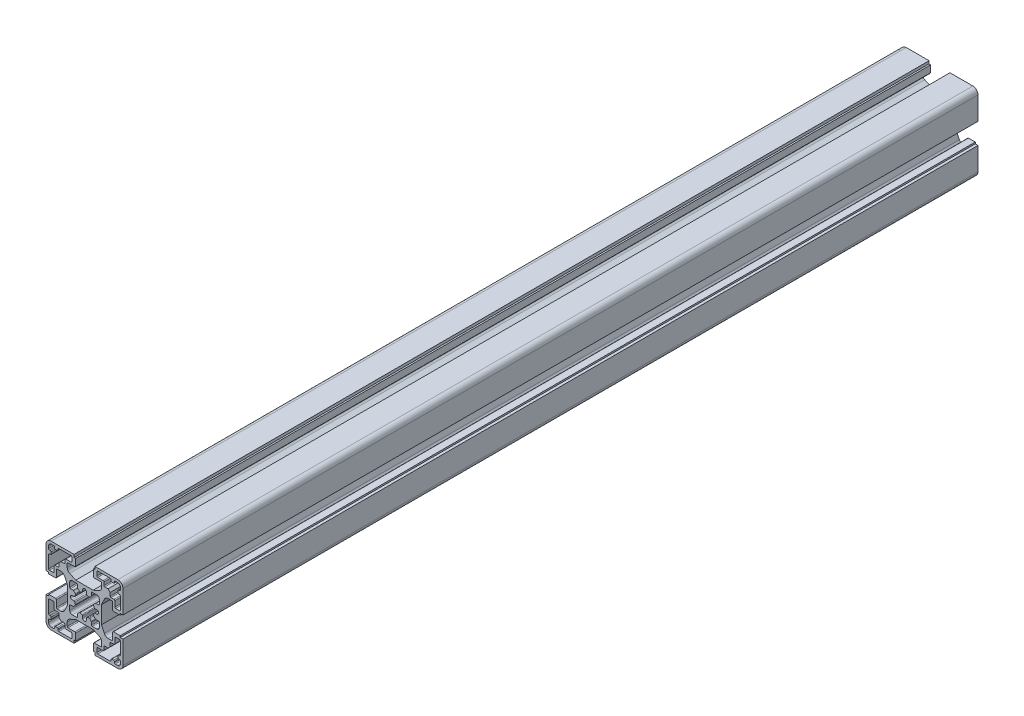
SolidWorks part; units mm, degrees
ref_plane "Alzado" through (0, 0, 0) normal (0, 0, 1) x (1, 0, 0)
ref_plane "Planta" through (0, 0, 0) normal (0, 1, 0) x (1, 0, 0)
ref_plane "Vista lateral" through (0, 0, 0) normal (1, 0, 0) x (0, 0, -1)
ref_plane "Plano1" through (0, 0, 1312.5) normal (0, 0, 1) x (1, 0, 0)
sketch "Croquis1" plane through (0, 0, 1312.5) normal (0, 0, 1) x (1, 0, 0)
  line L0 (13.7574, 15) -> (11.9, 15)
  line L1 (11.4, 15.5) -> (11.4, 17.25)
  line L2 (10.9, 17.75) -> (7.775, 17.75)
  line L3 (7.275, 18.25) -> (7.275, 20.5)
  line L4 (7.775, 21) -> (15, 21)
  line L5 (15.5, 20.5) -> (15.5, 20)
  line L6 (16, 19.5) -> (17, 19.5)
  line L7 (17.5, 20) -> (17.5, 20.5)
  line L8 (18, 21) -> (19.4, 21)
  line L9 (21, 19.4) -> (21, 18)
  line L10 (20.5, 17.5) -> (20, 17.5)
  line L11 (19.5, 17) -> (19.5, 16)
  line L12 (20, 15.5) -> (20.5, 15.5)
  line L13 (21, 15) -> (21, 7.775)
  line L14 (20.5, 7.275) -> (18.25, 7.275)
  line L15 (17.75, 7.775) -> (17.75, 10.9)
  line L16 (17.25, 11.4) -> (15.5, 11.4)
  line L17 (15, 11.9) -> (15, 13.7574)
  line L18 (15, 13.7574) -> (13.7574, 15)
  line L19 (-11.4, 17.25) -> (-11.4, 15.5)
  line L20 (-11.9, 15) -> (-13.7574, 15)
  line L21 (-13.7574, 15) -> (-15, 13.7574)
  line L22 (-15, 13.7574) -> (-15, 11.9)
  line L23 (-15.5, 11.4) -> (-17.25, 11.4)
  line L24 (-17.75, 10.9) -> (-17.75, 7.775)
  line L25 (-18.25, 7.275) -> (-20.5, 7.275)
  line L26 (-21, 7.775) -> (-21, 15)
  line L27 (-20.5, 15.5) -> (-20, 15.5)
  line L28 (-19.5, 16) -> (-19.5, 17)
  line L29 (-20, 17.5) -> (-20.5, 17.5)
  line L30 (-21, 18) -> (-21, 19.4)
  line L31 (-19.4, 21) -> (-18, 21)
  line L32 (-17.5, 20.5) -> (-17.5, 20)
  line L33 (-17, 19.5) -> (-16, 19.5)
  line L34 (-15.5, 20) -> (-15.5, 20.5)
  line L35 (-15, 21) -> (-7.775, 21)
  line L36 (-7.275, 20.5) -> (-7.275, 18.25)
  line L37 (-7.775, 17.75) -> (-10.9, 17.75)
  line L38 (-20.5, -7.275) -> (-18.25, -7.275)
  line L39 (-17.75, -7.775) -> (-17.75, -10.9)
  line L40 (-17.25, -11.4) -> (-15.5, -11.4)
  line L41 (-15, -11.9) -> (-15, -13.7574)
  line L42 (-15, -13.7574) -> (-13.7574, -15)
  line L43 (-13.7574, -15) -> (-11.9, -15)
  line L44 (-11.4, -15.5) -> (-11.4, -17.25)
  line L45 (-10.9, -17.75) -> (-7.775, -17.75)
  line L46 (-7.275, -18.25) -> (-7.275, -20.5)
  line L47 (-7.775, -21) -> (-15, -21)
  line L48 (-15.5, -20.5) -> (-15.5, -20)
  line L49 (-16, -19.5) -> (-17, -19.5)
  line L50 (-17.5, -20) -> (-17.5, -20.5)
  line L51 (-18, -21) -> (-19.4, -21)
  line L52 (-21, -19.4) -> (-21, -18)
  line L53 (-20.5, -17.5) -> (-20, -17.5)
  line L54 (-19.5, -17) -> (-19.5, -16)
  line L55 (-20, -15.5) -> (-20.5, -15.5)
  line L56 (-21, -15) -> (-21, -7.775)
  line L57 (-20.9, -6.1) -> (-22.5, -6.1)
  line L58 (-22.5, -6.1) -> (-22.5, -19.5)
  line L59 (-19.5, -22.5) -> (-6.1, -22.5)
  line L60 (-6.1, -22.5) -> (-6.1, -20.9)
  line L61 (-6.1, -20.9) -> (-5.175, -20.9)
  line L62 (-5.175, -20.9) -> (-5.175, -16.95)
  line L63 (-5.675, -16.45) -> (-9.6, -16.45)
  line L64 (-10.1, -15.95) -> (-10.1, -13.8742)
  line L65 (-8.6565, -11.6084) -> (-5.1, -9.95)
  line L66 (-5.1, -9.95) -> (5.1, -9.95)
  line L67 (5.1, -9.95) -> (8.6565, -11.6084)
  line L68 (10.1, -13.8742) -> (10.1, -15.95)
  line L69 (9.6, -16.45) -> (5.675, -16.45)
  line L70 (5.175, -16.95) -> (5.175, -20.9)
  line L71 (5.175, -20.9) -> (6.1, -20.9)
  line L72 (6.1, -20.9) -> (6.1, -22.5)
  line L73 (6.1, -22.5) -> (19.5, -22.5)
  line L74 (22.5, -19.5) -> (22.5, -6.1)
  line L75 (22.5, -6.1) -> (20.9, -6.1)
  line L76 (20.9, -6.1) -> (20.9, -5.175)
  line L77 (20.9, -5.175) -> (16.95, -5.175)
  line L78 (16.45, -5.675) -> (16.45, -9.6)
  line L79 (15.95, -10.1) -> (13.8742, -10.1)
  line L80 (11.6084, -8.6565) -> (9.95, -5.1)
  line L81 (9.95, -5.1) -> (9.95, 5.1)
  line L82 (9.95, 5.1) -> (11.6084, 8.6565)
  line L83 (13.8742, 10.1) -> (15.95, 10.1)
  line L84 (16.45, 9.6) -> (16.45, 5.675)
  line L85 (16.95, 5.175) -> (20.9, 5.175)
  line L86 (20.9, 5.175) -> (20.9, 6.1)
  line L87 (20.9, 6.1) -> (22.5, 6.1)
  line L88 (22.5, 6.1) -> (22.5, 19.5)
  line L89 (19.5, 22.5) -> (6.1, 22.5)
  line L90 (6.1, 22.5) -> (6.1, 20.9)
  line L91 (6.1, 20.9) -> (5.175, 20.9)
  line L92 (5.175, 20.9) -> (5.175, 16.95)
  line L93 (5.675, 16.45) -> (9.6, 16.45)
  line L94 (10.1, 15.95) -> (10.1, 13.8742)
  line L95 (8.6565, 11.6084) -> (5.1, 9.95)
  line L96 (5.1, 9.95) -> (-5.1, 9.95)
  line L97 (-5.1, 9.95) -> (-8.6565, 11.6084)
  line L98 (-10.1, 13.8742) -> (-10.1, 15.95)
  line L99 (-9.6, 16.45) -> (-5.675, 16.45)
  line L100 (-5.175, 16.95) -> (-5.175, 20.9)
  line L101 (-5.175, 20.9) -> (-6.1, 20.9)
  line L102 (-6.1, 20.9) -> (-6.1, 22.5)
  line L103 (-6.1, 22.5) -> (-19.5, 22.5)
  line L104 (-22.5, 19.5) -> (-22.5, 6.1)
  line L105 (-22.5, 6.1) -> (-20.9, 6.1)
  line L106 (-20.9, 6.1) -> (-20.9, 5.175)
  line L107 (-20.9, 5.175) -> (-16.95, 5.175)
  line L108 (-16.45, 5.675) -> (-16.45, 9.6)
  line L109 (-15.95, 10.1) -> (-13.8742, 10.1)
  line L110 (-11.6084, 8.6565) -> (-9.95, 5.1)
  line L111 (-9.95, 5.1) -> (-9.95, -5.1)
  line L112 (-9.95, -5.1) -> (-11.6084, -8.6565)
  line L113 (-13.8742, -10.1) -> (-15.95, -10.1)
  line L114 (-16.45, -9.6) -> (-16.45, -5.675)
  line L115 (-16.95, -5.175) -> (-20.9, -5.175)
  line L116 (-20.9, -5.175) -> (-20.9, -6.1)
  line L117 (-8.15, -4.1) -> (-6.7113, -4.1)
  line L118 (-6.3577, -3.9536) -> (-5.4141, -3.01)
  line L119 (-6.1451, -1.1) -> (-7.15, -1.1)
  line L120 (-7.15, 1.1) -> (-6.1451, 1.1)
  line L121 (-5.4141, 3.01) -> (-6.3577, 3.9536)
  line L122 (-6.7113, 4.1) -> (-8.15, 4.1)
  line L123 (-8.65, 4.6) -> (-8.65, 7.15)
  line L124 (-7.15, 8.65) -> (-4.6, 8.65)
  line L125 (-4.1, 8.15) -> (-4.1, 6.7113)
  line L126 (-3.9536, 6.3577) -> (-3.01, 5.4141)
  line L127 (-1.1, 6.1451) -> (-1.1, 7.15)
  line L128 (1.1, 7.15) -> (1.1, 6.1451)
  line L129 (3.01, 5.4141) -> (3.9536, 6.3577)
  line L130 (4.1, 6.7113) -> (4.1, 8.15)
  line L131 (4.6, 8.65) -> (7.15, 8.65)
  line L132 (8.65, 7.15) -> (8.65, 4.6)
  line L133 (8.15, 4.1) -> (6.7113, 4.1)
  line L134 (6.3577, 3.9536) -> (5.4141, 3.01)
  line L135 (6.1451, 1.1) -> (7.15, 1.1)
  line L136 (7.15, -1.1) -> (6.1451, -1.1)
  line L137 (5.4141, -3.01) -> (6.3577, -3.9536)
  line L138 (6.7113, -4.1) -> (8.15, -4.1)
  line L139 (8.65, -4.6) -> (8.65, -7.15)
  line L140 (7.15, -8.65) -> (4.6, -8.65)
  line L141 (4.1, -8.15) -> (4.1, -6.7113)
  line L142 (3.9536, -6.3577) -> (3.01, -5.4141)
  line L143 (1.1, -6.1451) -> (1.1, -7.15)
  line L144 (-1.1, -7.15) -> (-1.1, -6.1451)
  line L145 (-3.01, -5.4141) -> (-3.9536, -6.3577)
  line L146 (-4.1, -6.7113) -> (-4.1, -8.15)
  line L147 (-4.6, -8.65) -> (-7.15, -8.65)
  line L148 (-8.65, -7.15) -> (-8.65, -4.6)
  line L149 (11.9, -15) -> (13.7574, -15)
  line L150 (13.7574, -15) -> (15, -13.7574)
  line L151 (15, -13.7574) -> (15, -11.9)
  line L152 (15.5, -11.4) -> (17.25, -11.4)
  line L153 (17.75, -10.9) -> (17.75, -7.775)
  line L154 (18.25, -7.275) -> (20.5, -7.275)
  line L155 (21, -7.775) -> (21, -15)
  line L156 (20.5, -15.5) -> (20, -15.5)
  line L157 (19.5, -16) -> (19.5, -17)
  line L158 (20, -17.5) -> (20.5, -17.5)
  line L159 (21, -18) -> (21, -19.4)
  line L160 (19.4, -21) -> (18, -21)
  line L161 (17.5, -20.5) -> (17.5, -20)
  line L162 (17, -19.5) -> (16, -19.5)
  line L163 (15.5, -20) -> (15.5, -20.5)
  line L164 (15, -21) -> (7.775, -21)
  line L165 (7.275, -20.5) -> (7.275, -18.25)
  line L166 (7.775, -17.75) -> (10.9, -17.75)
  line L167 (11.4, -17.25) -> (11.4, -15.5)
  arc A0 (11.9, 15) -> (11.4, 15.5) centre (11.9, 15.5) cw
  arc A1 (11.4, 17.25) -> (10.9, 17.75) centre (10.9, 17.25) ccw
  arc A2 (7.775, 17.75) -> (7.275, 18.25) centre (7.775, 18.25) cw
  arc A3 (7.275, 20.5) -> (7.775, 21) centre (7.775, 20.5) cw
  arc A4 (15, 21) -> (15.5, 20.5) centre (15, 20.5) cw
  arc A5 (15.5, 20) -> (16, 19.5) centre (16, 20) ccw
  arc A6 (17, 19.5) -> (17.5, 20) centre (17, 20) ccw
  arc A7 (17.5, 20.5) -> (18, 21) centre (18, 20.5) cw
  arc A8 (19.4, 21) -> (21, 19.4) centre (19.4, 19.4) cw
  arc A9 (21, 18) -> (20.5, 17.5) centre (20.5, 18) cw
  arc A10 (20, 17.5) -> (19.5, 17) centre (20, 17) ccw
  arc A11 (19.5, 16) -> (20, 15.5) centre (20, 16) ccw
  arc A12 (20.5, 15.5) -> (21, 15) centre (20.5, 15) cw
  arc A13 (21, 7.775) -> (20.5, 7.275) centre (20.5, 7.775) cw
  arc A14 (18.25, 7.275) -> (17.75, 7.775) centre (18.25, 7.775) cw
  arc A15 (17.75, 10.9) -> (17.25, 11.4) centre (17.25, 10.9) ccw
  arc A16 (15.5, 11.4) -> (15, 11.9) centre (15.5, 11.9) cw
  arc A17 (-10.9, 17.75) -> (-11.4, 17.25) centre (-10.9, 17.25) ccw
  arc A18 (-11.4, 15.5) -> (-11.9, 15) centre (-11.9, 15.5) cw
  arc A19 (-15, 11.9) -> (-15.5, 11.4) centre (-15.5, 11.9) cw
  arc A20 (-17.25, 11.4) -> (-17.75, 10.9) centre (-17.25, 10.9) ccw
  arc A21 (-17.75, 7.775) -> (-18.25, 7.275) centre (-18.25, 7.775) cw
  arc A22 (-20.5, 7.275) -> (-21, 7.775) centre (-20.5, 7.775) cw
  arc A23 (-21, 15) -> (-20.5, 15.5) centre (-20.5, 15) cw
  arc A24 (-20, 15.5) -> (-19.5, 16) centre (-20, 16) ccw
  arc A25 (-19.5, 17) -> (-20, 17.5) centre (-20, 17) ccw
  arc A26 (-20.5, 17.5) -> (-21, 18) centre (-20.5, 18) cw
  arc A27 (-21, 19.4) -> (-19.4, 21) centre (-19.4, 19.4) cw
  arc A28 (-18, 21) -> (-17.5, 20.5) centre (-18, 20.5) cw
  arc A29 (-17.5, 20) -> (-17, 19.5) centre (-17, 20) ccw
  arc A30 (-16, 19.5) -> (-15.5, 20) centre (-16, 20) ccw
  arc A31 (-15.5, 20.5) -> (-15, 21) centre (-15, 20.5) cw
  arc A32 (-7.775, 21) -> (-7.275, 20.5) centre (-7.775, 20.5) cw
  arc A33 (-7.275, 18.25) -> (-7.775, 17.75) centre (-7.775, 18.25) cw
  arc A34 (-18.25, -7.275) -> (-17.75, -7.775) centre (-18.25, -7.775) cw
  arc A35 (-17.75, -10.9) -> (-17.25, -11.4) centre (-17.25, -10.9) ccw
  arc A36 (-15.5, -11.4) -> (-15, -11.9) centre (-15.5, -11.9) cw
  arc A37 (-11.9, -15) -> (-11.4, -15.5) centre (-11.9, -15.5) cw
  arc A38 (-11.4, -17.25) -> (-10.9, -17.75) centre (-10.9, -17.25) ccw
  arc A39 (-7.775, -17.75) -> (-7.275, -18.25) centre (-7.775, -18.25) cw
  arc A40 (-7.275, -20.5) -> (-7.775, -21) centre (-7.775, -20.5) cw
  arc A41 (-15, -21) -> (-15.5, -20.5) centre (-15, -20.5) cw
  arc A42 (-15.5, -20) -> (-16, -19.5) centre (-16, -20) ccw
  arc A43 (-17, -19.5) -> (-17.5, -20) centre (-17, -20) ccw
  arc A44 (-17.5, -20.5) -> (-18, -21) centre (-18, -20.5) cw
  arc A45 (-19.4, -21) -> (-21, -19.4) centre (-19.4, -19.4) cw
  arc A46 (-21, -18) -> (-20.5, -17.5) centre (-20.5, -18) cw
  arc A47 (-20, -17.5) -> (-19.5, -17) centre (-20, -17) ccw
  arc A48 (-19.5, -16) -> (-20, -15.5) centre (-20, -16) ccw
  arc A49 (-20.5, -15.5) -> (-21, -15) centre (-20.5, -15) cw
  arc A50 (-21, -7.775) -> (-20.5, -7.275) centre (-20.5, -7.775) cw
  arc A51 (-22.5, -19.5) -> (-19.5, -22.5) centre (-19.5, -19.5) ccw
  arc A52 (-5.175, -16.95) -> (-5.675, -16.45) centre (-5.675, -16.95) ccw
  arc A53 (-9.6, -16.45) -> (-10.1, -15.95) centre (-9.6, -15.95) cw
  arc A54 (-10.1, -13.8742) -> (-8.6565, -11.6084) centre (-7.6, -13.8742) cw
  arc A55 (8.6565, -11.6084) -> (10.1, -13.8742) centre (7.6, -13.8742) cw
  arc A56 (10.1, -15.95) -> (9.6, -16.45) centre (9.6, -15.95) cw
  arc A57 (5.675, -16.45) -> (5.175, -16.95) centre (5.675, -16.95) ccw
  arc A58 (19.5, -22.5) -> (22.5, -19.5) centre (19.5, -19.5) ccw
  arc A59 (16.95, -5.175) -> (16.45, -5.675) centre (16.95, -5.675) ccw
  arc A60 (16.45, -9.6) -> (15.95, -10.1) centre (15.95, -9.6) cw
  arc A61 (13.8742, -10.1) -> (11.6084, -8.6565) centre (13.8742, -7.6) cw
  arc A62 (11.6084, 8.6565) -> (13.8742, 10.1) centre (13.8742, 7.6) cw
  arc A63 (15.95, 10.1) -> (16.45, 9.6) centre (15.95, 9.6) cw
  arc A64 (16.45, 5.675) -> (16.95, 5.175) centre (16.95, 5.675) ccw
  arc A65 (22.5, 19.5) -> (19.5, 22.5) centre (19.5, 19.5) ccw
  arc A66 (5.175, 16.95) -> (5.675, 16.45) centre (5.675, 16.95) ccw
  arc A67 (9.6, 16.45) -> (10.1, 15.95) centre (9.6, 15.95) cw
  arc A68 (10.1, 13.8742) -> (8.6565, 11.6084) centre (7.6, 13.8742) cw
  arc A69 (-8.6565, 11.6084) -> (-10.1, 13.8742) centre (-7.6, 13.8742) cw
  arc A70 (-10.1, 15.95) -> (-9.6, 16.45) centre (-9.6, 15.95) cw
  arc A71 (-5.675, 16.45) -> (-5.175, 16.95) centre (-5.675, 16.95) ccw
  arc A72 (-19.5, 22.5) -> (-22.5, 19.5) centre (-19.5, 19.5) ccw
  arc A73 (-16.95, 5.175) -> (-16.45, 5.675) centre (-16.95, 5.675) ccw
  arc A74 (-16.45, 9.6) -> (-15.95, 10.1) centre (-15.95, 9.6) cw
  arc A75 (-13.8742, 10.1) -> (-11.6084, 8.6565) centre (-13.8742, 7.6) cw
  arc A76 (-11.6084, -8.6565) -> (-13.8742, -10.1) centre (-13.8742, -7.6) cw
  arc A77 (-15.95, -10.1) -> (-16.45, -9.6) centre (-15.95, -9.6) cw
  arc A78 (-16.45, -5.675) -> (-16.95, -5.175) centre (-16.95, -5.675) ccw
  arc A79 (-6.7113, -4.1) -> (-6.3577, -3.9536) centre (-6.7113, -3.6) ccw
  arc A80 (-5.4141, -3.01) -> (-5.3135, -2.4472) centre (-5.7677, -2.6564) ccw
  arc A81 (-5.3135, -2.4472) -> (-5.6613, -1.474) centre (0, 0) cw
  arc A82 (-5.6613, -1.474) -> (-6.1451, -1.1) centre (-6.1451, -1.6) ccw
  arc A83 (-7.15, -1.1) -> (-7.15, 1.1) centre (-7.15, 0) cw
  arc A84 (-6.1451, 1.1) -> (-5.6613, 1.474) centre (-6.1451, 1.6) ccw
  arc A85 (-5.6613, 1.474) -> (-5.3135, 2.4472) centre (0, 0) cw
  arc A86 (-5.3135, 2.4472) -> (-5.4141, 3.01) centre (-5.7677, 2.6564) ccw
  arc A87 (-6.3577, 3.9536) -> (-6.7113, 4.1) centre (-6.7113, 3.6) ccw
  arc A88 (-8.15, 4.1) -> (-8.65, 4.6) centre (-8.15, 4.6) cw
  arc A89 (-8.65, 7.15) -> (-7.15, 8.65) centre (-7.15, 7.15) cw
  arc A90 (-4.6, 8.65) -> (-4.1, 8.15) centre (-4.6, 8.15) cw
  arc A91 (-4.1, 6.7113) -> (-3.9536, 6.3577) centre (-3.6, 6.7113) ccw
  arc A92 (-3.01, 5.4141) -> (-2.4472, 5.3135) centre (-2.6564, 5.7677) ccw
  arc A93 (-2.4472, 5.3135) -> (-1.474, 5.6613) centre (0, 0) cw
  arc A94 (-1.474, 5.6613) -> (-1.1, 6.1451) centre (-1.6, 6.1451) ccw
  arc A95 (-1.1, 7.15) -> (1.1, 7.15) centre (0, 7.15) cw
  arc A96 (1.1, 6.1451) -> (1.474, 5.6613) centre (1.6, 6.1451) ccw
  arc A97 (1.474, 5.6613) -> (2.4472, 5.3135) centre (0, 0) cw
  arc A98 (2.4472, 5.3135) -> (3.01, 5.4141) centre (2.6564, 5.7677) ccw
  arc A99 (3.9536, 6.3577) -> (4.1, 6.7113) centre (3.6, 6.7113) ccw
  arc A100 (4.1, 8.15) -> (4.6, 8.65) centre (4.6, 8.15) cw
  arc A101 (7.15, 8.65) -> (8.65, 7.15) centre (7.15, 7.15) cw
  arc A102 (8.65, 4.6) -> (8.15, 4.1) centre (8.15, 4.6) cw
  arc A103 (6.7113, 4.1) -> (6.3577, 3.9536) centre (6.7113, 3.6) ccw
  arc A104 (5.4141, 3.01) -> (5.3135, 2.4472) centre (5.7677, 2.6564) ccw
  arc A105 (5.3135, 2.4472) -> (5.6613, 1.474) centre (0, 0) cw
  arc A106 (5.6613, 1.474) -> (6.1451, 1.1) centre (6.1451, 1.6) ccw
  arc A107 (7.15, 1.1) -> (7.15, -1.1) centre (7.15, 0) cw
  arc A108 (6.1451, -1.1) -> (5.6613, -1.474) centre (6.1451, -1.6) ccw
  arc A109 (5.6613, -1.474) -> (5.3135, -2.4472) centre (0, 0) cw
  arc A110 (5.3135, -2.4472) -> (5.4141, -3.01) centre (5.7677, -2.6564) ccw
  arc A111 (6.3577, -3.9536) -> (6.7113, -4.1) centre (6.7113, -3.6) ccw
  arc A112 (8.15, -4.1) -> (8.65, -4.6) centre (8.15, -4.6) cw
  arc A113 (8.65, -7.15) -> (7.15, -8.65) centre (7.15, -7.15) cw
  arc A114 (4.6, -8.65) -> (4.1, -8.15) centre (4.6, -8.15) cw
  arc A115 (4.1, -6.7113) -> (3.9536, -6.3577) centre (3.6, -6.7113) ccw
  arc A116 (3.01, -5.4141) -> (2.4472, -5.3135) centre (2.6564, -5.7677) ccw
  arc A117 (2.4472, -5.3135) -> (1.474, -5.6613) centre (0, 0) cw
  arc A118 (1.474, -5.6613) -> (1.1, -6.1451) centre (1.6, -6.1451) ccw
  arc A119 (1.1, -7.15) -> (-1.1, -7.15) centre (0, -7.15) cw
  arc A120 (-1.1, -6.1451) -> (-1.474, -5.6613) centre (-1.6, -6.1451) ccw
  arc A121 (-1.474, -5.6613) -> (-2.4472, -5.3135) centre (0, 0) cw
  arc A122 (-2.4472, -5.3135) -> (-3.01, -5.4141) centre (-2.6564, -5.7677) ccw
  arc A123 (-3.9536, -6.3577) -> (-4.1, -6.7113) centre (-3.6, -6.7113) ccw
  arc A124 (-4.1, -8.15) -> (-4.6, -8.65) centre (-4.6, -8.15) cw
  arc A125 (-7.15, -8.65) -> (-8.65, -7.15) centre (-7.15, -7.15) cw
  arc A126 (-8.65, -4.6) -> (-8.15, -4.1) centre (-8.15, -4.6) cw
  arc A127 (11.4, -15.5) -> (11.9, -15) centre (11.9, -15.5) cw
  arc A128 (15, -11.9) -> (15.5, -11.4) centre (15.5, -11.9) cw
  arc A129 (17.25, -11.4) -> (17.75, -10.9) centre (17.25, -10.9) ccw
  arc A130 (17.75, -7.775) -> (18.25, -7.275) centre (18.25, -7.775) cw
  arc A131 (20.5, -7.275) -> (21, -7.775) centre (20.5, -7.775) cw
  arc A132 (21, -15) -> (20.5, -15.5) centre (20.5, -15) cw
  arc A133 (20, -15.5) -> (19.5, -16) centre (20, -16) ccw
  arc A134 (19.5, -17) -> (20, -17.5) centre (20, -17) ccw
  arc A135 (20.5, -17.5) -> (21, -18) centre (20.5, -18) cw
  arc A136 (21, -19.4) -> (19.4, -21) centre (19.4, -19.4) cw
  arc A137 (18, -21) -> (17.5, -20.5) centre (18, -20.5) cw
  arc A138 (17.5, -20) -> (17, -19.5) centre (17, -20) ccw
  arc A139 (16, -19.5) -> (15.5, -20) centre (16, -20) ccw
  arc A140 (15.5, -20.5) -> (15, -21) centre (15, -20.5) cw
  arc A141 (7.775, -21) -> (7.275, -20.5) centre (7.775, -20.5) cw
  arc A142 (7.275, -18.25) -> (7.775, -17.75) centre (7.775, -18.25) cw
  arc A143 (10.9, -17.75) -> (11.4, -17.25) centre (10.9, -17.25) ccw
extrude "Saliente-Extruir1" add sketch "Croquis1" against normal blind 500
